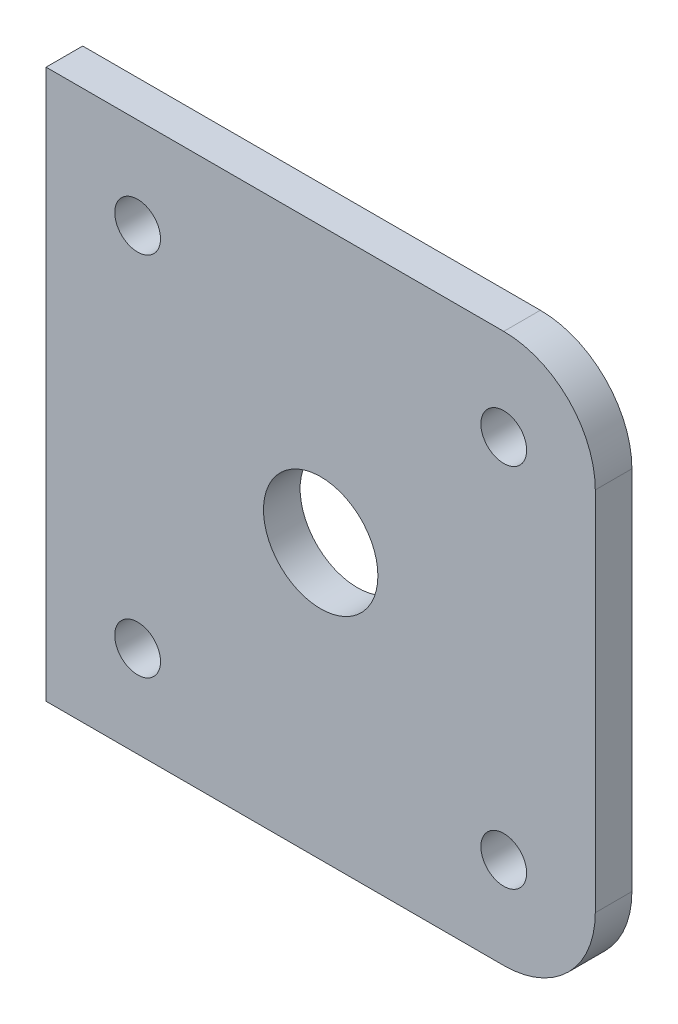
SolidWorks part; units mm, degrees
ref_plane "Front Plane" through (0, 0, 0) normal (0, 0, 1) x (1, 0, 0)
ref_plane "Top Plane" through (0, 0, 0) normal (0, 1, 0) x (1, 0, 0)
ref_plane "Right Plane" through (0, 0, 0) normal (1, 0, 0) x (0, 0, -1)
sketch "Sketch2" plane through (0, 0, 0) normal (0, 0, 1) x (1, 0, 0)
  line L1 (-60, -60) -> (60, -60)
  line L2 (-60, -60) -> (-60, 60)
  line L3 (-60, 60) -> (60, 60)
  line L4 (60, -60) -> (60, 60)
  line L5 (-60, -60) -> (60, 60) construction
  line L6 (-60, 60) -> (60, -60) construction
  point P0 (0, 0)
  dimension "D1" = 120
extrude "Boss-Extrude1" add sketch "Sketch2" along normal blind 8
sketch "Sketch3" plane through (0, 0, 8) normal (0, 0, 1) x (1, 0, 0)
  circle A0 centre (0, 0) radius 7.62
sketch "Sketch4" plane through (0, 0, 8) normal (0, 0, 1) x (1, 0, 0)
  circle A1 centre (0, 0) radius 12.5
  dimension "D1" = 25
extrude "Cut-Extrude1" cut sketch "Sketch4" against normal through all contours A1
sketch "Sketch6" plane through (0, 0, 8) normal (0, 0, 1) x (1, 0, 0)
  line L0 (-60, 60) -> (-60, -60) construction
  line L1 (60, 60) -> (-60, 60) construction
  circle A0 centre (-40, 40) radius 5
  dimension "D1" = 20
  dimension "D3" = 10
  dimension "D2" = 20
extrude "Cut-Extrude2" cut sketch "Sketch6" against normal through all
pattern_linear "LPattern1" count 2 spacing 80 along (1, 0, 0) count 2 spacing 80 along (0, -1, 0) of "Cut-Extrude2"
fillet "Fillet2" radius 20 2 edges at (60, 60, 4) (60, -60, 4)
